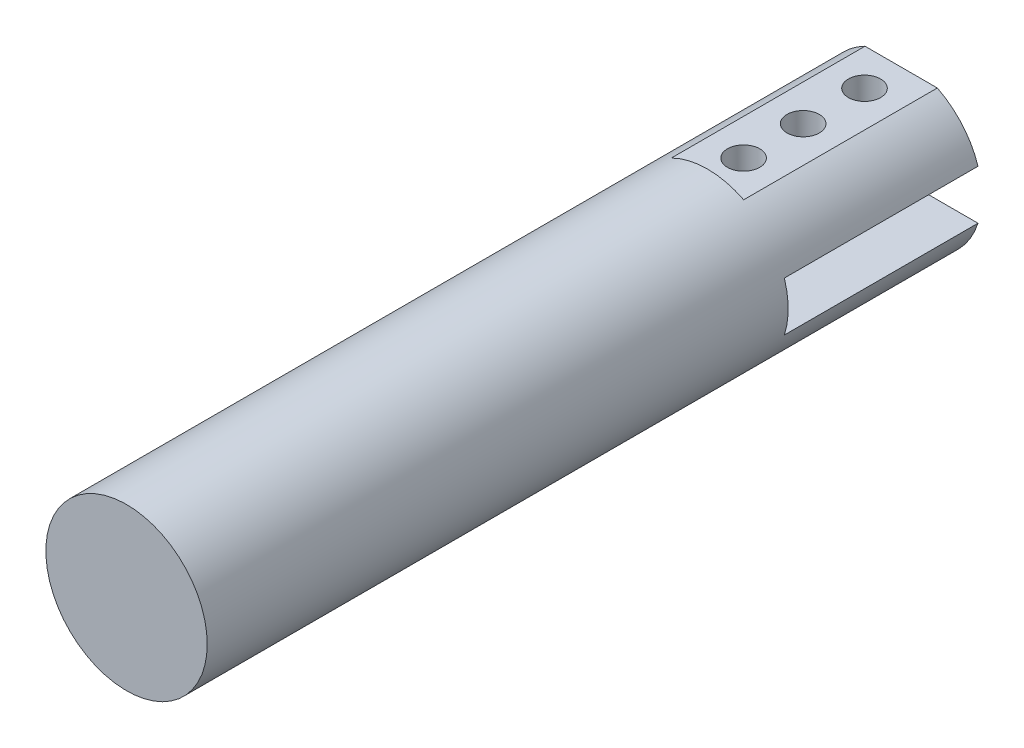
SolidWorks part; units mm, degrees
ref_plane "Спереди" through (0, 0, 0) normal (0, 0, 1) x (1, 0, 0)
ref_plane "Сверху" through (0, 0, 0) normal (0, 1, 0) x (1, 0, 0)
ref_plane "Справа" through (0, 0, 0) normal (1, 0, 0) x (0, 0, -1)
sketch "Эскиз1" plane through (0, 0, 0) normal (0, 0, 1) x (1, 0, 0)
  circle A0 centre (0, 0) radius 12.5
extrude "Вытянуть1" add sketch "Эскиз1" along normal blind 120
sketch "Эскиз2" plane through (0, 0, 0) normal (0, 0, -1) x (-1, 0, 0)
  line L1 (-35.1005, 3.82) -> (35.1005, 3.82)
  line L2 (-35.1005, 3.82) -> (-35.1005, -3.82)
  line L3 (-35.1005, -3.82) -> (35.1005, -3.82)
  line L4 (35.1005, 3.82) -> (35.1005, -3.82)
  line L5 (-35.1005, 3.82) -> (35.1005, -3.82) construction
  line L6 (-35.1005, -3.82) -> (35.1005, 3.82) construction
  point P0 (0, 0)
extrude "Вытянуть2" cut sketch "Эскиз2" against normal blind 30
sketch "Эскиз4" plane through (0, 0, 0) normal (0, 1, 0) x (1, 0, 0)
  circle A0 centre (0, -5.6806) radius 2.5
  circle A1 centre (0, -15.1858) radius 2.5
  circle A2 centre (0, -24.4088) radius 2.5
extrude "Вырез-Вытянуть1" cut sketch "Эскиз4" against normal mid plane 70
sketch "Эскиз5" plane through (0, 0, 0) normal (0, 0, -1) x (-1, 0, 0)
  line L0 (0, 0) -> (20.7443, 0) construction
  line L1 (-16.1733, -11.1738) -> (17.6231, -11.1738)
  line L2 (-16.1733, 17.6731) -> (17.6231, 17.6731)
  line L3 (-16.1733, 17.6731) -> (-16.1733, 11.1738)
  line L4 (-16.1733, 11.1738) -> (17.6231, 11.1738)
  line L5 (17.6231, 17.6731) -> (17.6231, 11.1738)
  line L6 (17.6231, -17.6731) -> (17.6231, -11.1738)
  line L7 (-16.1733, -17.6731) -> (-16.1733, -11.1738)
  line L8 (-16.1733, -17.6731) -> (17.6231, -17.6731)
extrude "Вытянуть4" cut sketch "Эскиз5" against normal blind 30
